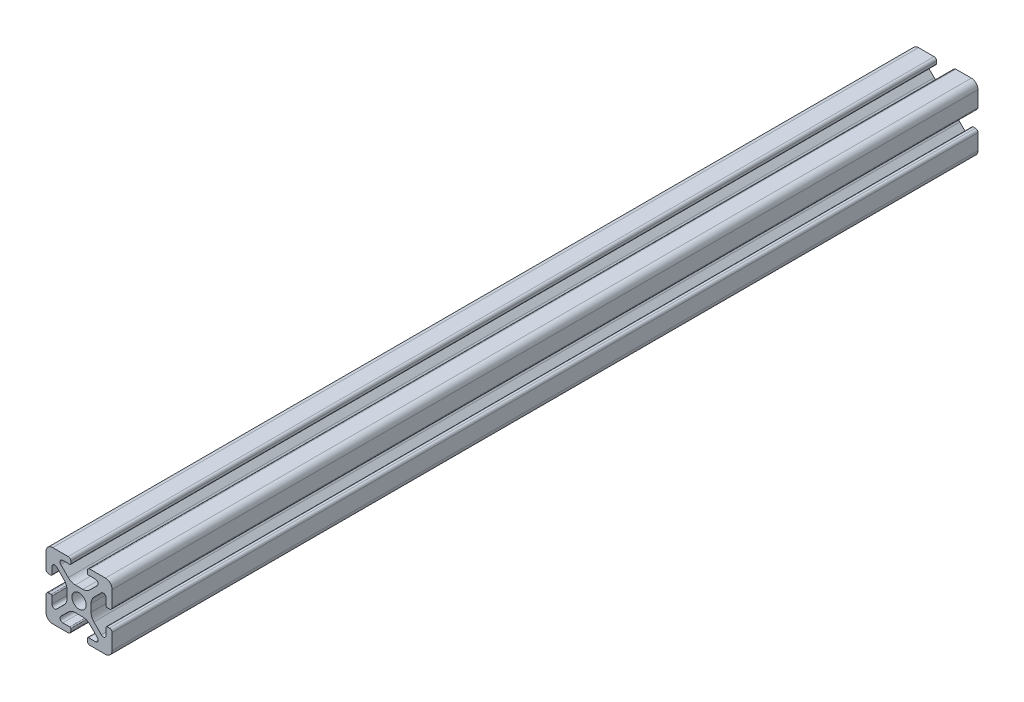
SolidWorks part; units mm, degrees
ref_plane "Front Plane" through (0, 0, 0) normal (0, 0, 1) x (1, 0, 0)
ref_plane "Top Plane" through (0, 0, 0) normal (0, 1, 0) x (1, 0, 0)
ref_plane "Right Plane" through (0, 0, 0) normal (1, 0, 0) x (0, 0, -1)
sketch "Sketch1" plane through (0, 0, 0) normal (0, 0, 1) x (1, 0, 0)
  line L2 (-9.9949, 7.9883) -> (-9.9949, 3.2893)
  line L3 (-7.9883, 9.9949) -> (-3.2893, 9.9949)
  line L4 (-2.5019, 9.2075) -> (-2.5019, 8.4963)
  line L5 (-2.8067, 8.1915) -> (-4.9149, 8.1915)
  line L6 (-5.5076, 6.7606) -> (-3.2528, 4.5058)
  line L7 (-6.7606, 5.5076) -> (-4.5058, 3.2528)
  line L8 (-8.1915, 4.9149) -> (-8.1915, 2.8067)
  line L9 (-8.4963, 2.5019) -> (-9.2075, 2.5019)
  line L11 (-1.1334, 3.6279) -> (1.1334, 3.6279)
  line L12 (-3.6279, 1.1334) -> (-3.6279, -1.1334)
  line L13 (8.4963, 2.5019) -> (9.2075, 2.5019)
  line L14 (8.1915, 4.9149) -> (8.1915, 2.8067)
  line L15 (9.9949, 7.9883) -> (9.9949, 3.2893)
  line L16 (7.9883, 9.9949) -> (3.2893, 9.9949)
  line L17 (2.5019, 9.2075) -> (2.5019, 8.4963)
  line L18 (2.8067, 8.1915) -> (4.9149, 8.1915)
  line L19 (3.6279, 1.1334) -> (3.6279, -1.1334)
  line L20 (5.5076, 6.7606) -> (3.2528, 4.5058)
  line L21 (6.7606, 5.5076) -> (4.5058, 3.2528)
  line L22 (-8.4963, -2.5019) -> (-9.2075, -2.5019)
  line L23 (-8.1915, -4.9149) -> (-8.1915, -2.8067)
  line L24 (-6.7606, -5.5076) -> (-4.5058, -3.2528)
  line L25 (-5.5076, -6.7606) -> (-3.2528, -4.5058)
  line L26 (-2.8067, -8.1915) -> (-4.9149, -8.1915)
  line L27 (-2.5019, -9.2075) -> (-2.5019, -8.4963)
  line L28 (-7.9883, -9.9949) -> (-3.2893, -9.9949)
  line L29 (-9.9949, -7.9883) -> (-9.9949, -3.2893)
  line L30 (9.9949, -7.9883) -> (9.9949, -3.2893)
  line L31 (7.9883, -9.9949) -> (3.2893, -9.9949)
  line L32 (2.5019, -9.2075) -> (2.5019, -8.4963)
  line L33 (2.8067, -8.1915) -> (4.9149, -8.1915)
  line L34 (5.5076, -6.7606) -> (3.2528, -4.5058)
  line L35 (6.7606, -5.5076) -> (4.5058, -3.2528)
  line L36 (8.1915, -4.9149) -> (8.1915, -2.8067)
  line L37 (8.4963, -2.5019) -> (9.2075, -2.5019)
  line L38 (-1.1334, -3.6279) -> (1.1334, -3.6279)
  circle A0 centre (0, 0) radius 2.1463
  arc A1 (-9.9949, 7.9883) -> (-7.9883, 9.9949) centre (-7.9883, 7.9883) cw
  arc A2 (-6.7606, 5.5076) -> (-8.1915, 4.9149) centre (-7.3533, 4.9149) ccw
  arc A3 (-4.9149, 8.1915) -> (-5.5076, 6.7606) centre (-4.9149, 7.3533) ccw
  arc A4 (-3.2893, 9.9949) -> (-2.5019, 9.2075) centre (-3.2893, 9.2075) cw
  arc A5 (-9.9949, 3.2893) -> (-9.2075, 2.5019) centre (-9.2075, 3.2893) ccw
  arc A6 (-8.1915, 2.8067) -> (-8.4963, 2.5019) centre (-8.4963, 2.8067) cw
  arc A7 (-2.5019, 8.4963) -> (-2.8067, 8.1915) centre (-2.8067, 8.4963) cw
  arc A8 (-1.1334, 3.6279) -> (-3.2528, 4.5058) centre (-1.1334, 6.6251) cw
  arc A9 (-3.6279, 1.1334) -> (-4.5058, 3.2528) centre (-6.6251, 1.1334) ccw
  arc A10 (8.1915, 2.8067) -> (8.4963, 2.5019) centre (8.4963, 2.8067) ccw
  arc A11 (9.9949, 3.2893) -> (9.2075, 2.5019) centre (9.2075, 3.2893) cw
  arc A12 (9.9949, 7.9883) -> (7.9883, 9.9949) centre (7.9883, 7.9883) ccw
  arc A13 (3.2893, 9.9949) -> (2.5019, 9.2075) centre (3.2893, 9.2075) ccw
  arc A14 (2.5019, 8.4963) -> (2.8067, 8.1915) centre (2.8067, 8.4963) ccw
  arc A15 (1.1334, 3.6279) -> (3.2528, 4.5058) centre (1.1334, 6.6251) ccw
  arc A16 (3.6279, 1.1334) -> (4.5058, 3.2528) centre (6.6251, 1.1334) cw
  arc A17 (6.7606, 5.5076) -> (8.1915, 4.9149) centre (7.3533, 4.9149) cw
  arc A18 (4.9149, 8.1915) -> (5.5076, 6.7606) centre (4.9149, 7.3533) cw
  arc A19 (-3.6279, -1.1334) -> (-4.5058, -3.2528) centre (-6.6251, -1.1334) cw
  arc A20 (-1.1334, -3.6279) -> (-3.2528, -4.5058) centre (-1.1334, -6.6251) ccw
  arc A21 (-2.5019, -8.4963) -> (-2.8067, -8.1915) centre (-2.8067, -8.4963) ccw
  arc A22 (-8.1915, -2.8067) -> (-8.4963, -2.5019) centre (-8.4963, -2.8067) ccw
  arc A23 (-9.9949, -3.2893) -> (-9.2075, -2.5019) centre (-9.2075, -3.2893) cw
  arc A24 (-3.2893, -9.9949) -> (-2.5019, -9.2075) centre (-3.2893, -9.2075) ccw
  arc A25 (-4.9149, -8.1915) -> (-5.5076, -6.7606) centre (-4.9149, -7.3533) cw
  arc A26 (-6.7606, -5.5076) -> (-8.1915, -4.9149) centre (-7.3533, -4.9149) cw
  arc A27 (-9.9949, -7.9883) -> (-7.9883, -9.9949) centre (-7.9883, -7.9883) ccw
  arc A28 (9.9949, -7.9883) -> (7.9883, -9.9949) centre (7.9883, -7.9883) cw
  arc A29 (6.7606, -5.5076) -> (8.1915, -4.9149) centre (7.3533, -4.9149) ccw
  arc A30 (4.9149, -8.1915) -> (5.5076, -6.7606) centre (4.9149, -7.3533) ccw
  arc A31 (3.2893, -9.9949) -> (2.5019, -9.2075) centre (3.2893, -9.2075) cw
  arc A32 (9.9949, -3.2893) -> (9.2075, -2.5019) centre (9.2075, -3.2893) ccw
  arc A33 (8.1915, -2.8067) -> (8.4963, -2.5019) centre (8.4963, -2.8067) cw
  arc A34 (2.5019, -8.4963) -> (2.8067, -8.1915) centre (2.8067, -8.4963) cw
  arc A35 (1.1334, -3.6279) -> (3.2528, -4.5058) centre (1.1334, -6.6251) cw
  arc A36 (3.6279, -1.1334) -> (4.5058, -3.2528) centre (6.6251, -1.1334) ccw
extrude "Boss-Extrude1" add sketch "Sketch1" along normal mid plane 261.9375
